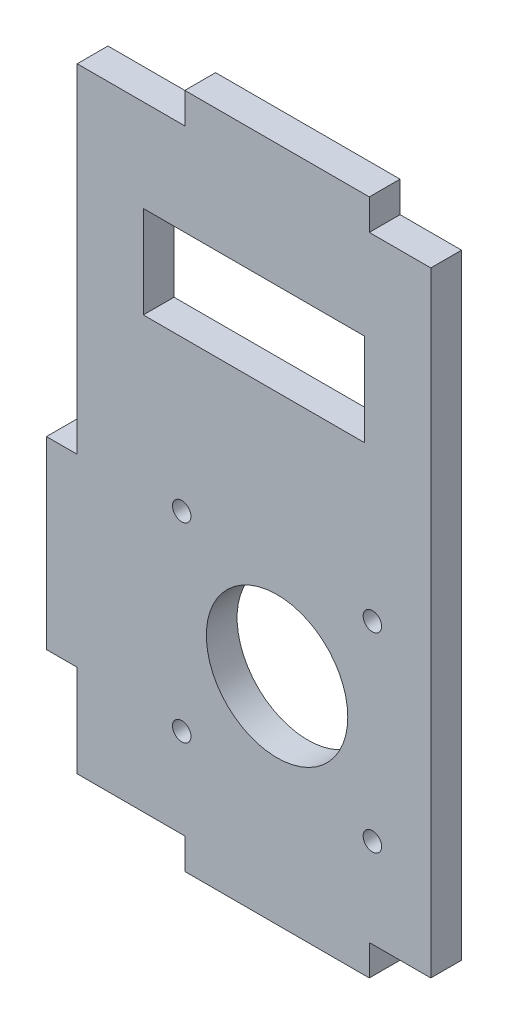
SolidWorks part; units mm, degrees
ref_plane "前视基准面" through (0, 0, 0) normal (0, 0, 1) x (1, 0, 0)
ref_plane "上视基准面" through (0, 0, 0) normal (0, 1, 0) x (1, 0, 0)
ref_plane "右视基准面" through (0, 0, 0) normal (1, 0, 0) x (0, 0, -1)
sketch "草图1" plane through (0, 0, 0) normal (0, 0, 1) x (1, 0, 0)
  line L0 (-2.5, 100) -> (15, 100)
  line L1 (-2.5, 0) -> (15, 0)
  line L2 (55, 100) -> (55, 0)
  line L3 (-2.5, 68.51) -> (-2.5, -3.8177) construction
  line L4 (55, 0) -> (45, 0)
  line L5 (-7.5, 15) -> (-2.5, 15)
  line L6 (15, 0) -> (15, -5)
  line L7 (15, -5) -> (45, -5)
  line L8 (45, 0) -> (45, -5)
  line L9 (-2.5, 15) -> (-2.5, 0)
  line L10 (-7.5, 15) -> (-7.5, 45)
  line L11 (-7.5, 45) -> (-2.5, 45)
  line L12 (-2.5, 45) -> (-2.5, 100)
  line L13 (45, 100) -> (45, 105)
  line L14 (30, 65.6077) -> (30, -18.5627) construction
  line L15 (15, 105) -> (15, 100)
  line L16 (45, 105) -> (15, 105)
  line L17 (45, 100) -> (55, 100)
  line L19 (14.5, 45.5) -> (45.5, 45.5) construction
  line L20 (14.5, 45.5) -> (14.5, 14.5) construction
  line L21 (14.5, 14.5) -> (45.5, 14.5) construction
  line L22 (45.5, 45.5) -> (45.5, 14.5) construction
  line L23 (14.5, 45.5) -> (45.5, 14.5) construction
  line L24 (14.5, 14.5) -> (45.5, 45.5) construction
  line L25 (8.25, 85) -> (44.25, 85)
  line L26 (8.25, 85) -> (8.25, 70)
  line L27 (8.25, 70) -> (44.25, 70)
  line L28 (44.25, 85) -> (44.25, 70)
  circle A0 centre (30, 30) radius 11.5
  circle A1 centre (14.5, 45.5) radius 1.5
  circle A2 centre (45.5, 45.5) radius 1.5
  circle A3 centre (45.5, 14.5) radius 1.5
  circle A4 centre (14.5, 14.5) radius 1.5
  dimension "D13" = 23
  dimension "D15" = 17.5
  dimension "D2" = 15
  dimension "D3" = 30
  dimension "D4" = 5
  dimension "D5" = 100
  dimension "D6" = 10
  dimension "D7" = 5
  dimension "D8" = 30
  dimension "D9" = 30
  dimension "D10" = 15
  dimension "D11" = 10
  dimension "D12" = 30
  dimension "D14" = 31
  dimension "D16" = 17.5
  dimension "D17" = 5
  dimension "D18" = 15
  dimension "D19" = 36
  dimension "D20" = 57.5
  dimension "D21" = 10.75
  dimension "D22" = 15
extrude "凸台-拉伸1" add sketch "草图1" along normal blind 5
